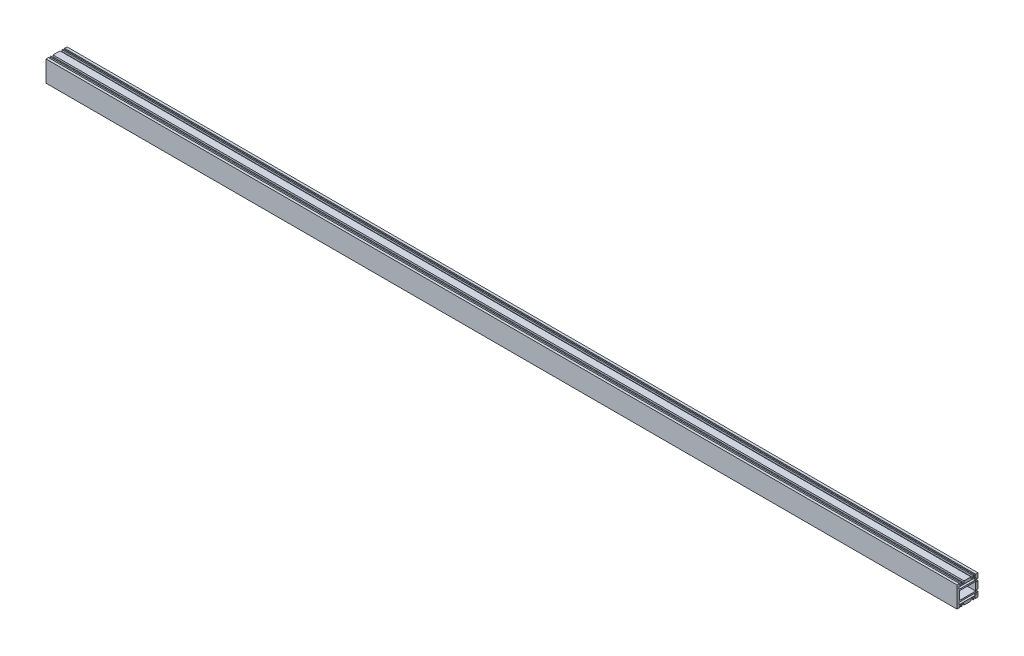
SolidWorks part; units mm, degrees
ref_plane "前视基准面" through (0, 0, 0) normal (0, 0, 1) x (1, 0, 0)
ref_plane "上视基准面" through (0, 0, 0) normal (0, 1, 0) x (1, 0, 0)
ref_plane "右视基准面" through (0, 0, 0) normal (1, 0, 0) x (0, 0, -1)
sketch "草图1" plane through (0, 0, 0) normal (1, 0, 0) x (0, 0, -1)
  line L0 (-15, 15) -> (15, -15) construction
  line L1 (-15, 15) -> (-11.5, 15)
  line L2 (-15, 15) -> (-15, -15)
  line L3 (-15, -15) -> (-11.5, -15)
  line L4 (15, 15) -> (15, 8)
  line L5 (15, 15) -> (-15, -15) construction
  line L6 (-11.5, 15) -> (-11.5, 13.5)
  line L7 (-11.5, 13.5) -> (-11, 13.5)
  line L8 (-11, 13.5) -> (-11, 12)
  line L9 (-11, 12) -> (-9.5, 12)
  line L10 (-9.5, 12) -> (-9.5, 15)
  line L11 (-9.5, 15) -> (-8, 15)
  line L12 (-8, 15) -> (-8, 12.5)
  line L13 (-8, 12.5) -> (-5, 12.5)
  line L14 (-5, 12.5) -> (-5, 15)
  line L15 (-5, 15) -> (5, 15)
  line L16 (0, 21.5201) -> (0, -18.309) construction
  line L17 (0, 55) -> (0, -55) construction
  line L18 (5, 12.5) -> (5, 15)
  line L19 (8, 12.5) -> (5, 12.5)
  line L20 (8, 15) -> (8, 12.5)
  line L21 (9.5, 15) -> (8, 15)
  line L22 (9.5, 12) -> (9.5, 15)
  line L23 (11, 12) -> (9.5, 12)
  line L24 (11, 13.5) -> (11, 12)
  line L25 (11.5, 13.5) -> (11, 13.5)
  line L26 (11.5, 15) -> (11.5, 13.5)
  line L27 (8, 15) -> (9.5, 15)
  line L28 (11.5, 15) -> (15, 15)
  line L29 (-19.8303, 0) -> (22.13, 0) construction
  line L30 (55, 0) -> (-55, 0) construction
  line L31 (8, -15) -> (9.5, -15)
  line L32 (11.5, -15) -> (11.5, -13.5)
  line L33 (11.5, -13.5) -> (11, -13.5)
  line L34 (11, -13.5) -> (11, -12)
  line L35 (11, -12) -> (9.5, -12)
  line L36 (9.5, -12) -> (9.5, -15)
  line L37 (9.5, -15) -> (8, -15)
  line L38 (8, -15) -> (8, -12.5)
  line L39 (8, -12.5) -> (5, -12.5)
  line L40 (5, -12.5) -> (5, -15)
  line L41 (-5, -15) -> (5, -15)
  line L42 (-5, -12.5) -> (-5, -15)
  line L43 (-8, -12.5) -> (-5, -12.5)
  line L44 (-8, -15) -> (-8, -12.5)
  line L45 (-9.5, -15) -> (-8, -15)
  line L46 (-9.5, -12) -> (-9.5, -15)
  line L47 (-11, -12) -> (-9.5, -12)
  line L48 (-11, -13.5) -> (-11, -12)
  line L49 (-11.5, -13.5) -> (-11, -13.5)
  line L50 (-11.5, -15) -> (-11.5, -13.5)
  line L51 (-9.5, -15) -> (-8, -15)
  line L52 (-5, -15) -> (5, -15)
  line L53 (8, -15) -> (9.5, -15)
  line L54 (11.5, -15) -> (15, -15)
  line L55 (15, 8) -> (12.5, 8)
  line L56 (12.5, 8) -> (12.5, 5)
  line L57 (12.5, 5) -> (15, 5)
  line L58 (12.5, -5) -> (15, -5)
  line L59 (12.5, -8) -> (12.5, -5)
  line L60 (15, -8) -> (12.5, -8)
  line L61 (15, 5) -> (15, -5)
  line L62 (15, -8) -> (15, -15)
  line L63 (12, -10.5) -> (12, -8.5)
  line L64 (-11.5, 11) -> (11.5, 11)
  line L65 (-12, 10.5) -> (-12, 8.5)
  line L66 (-11.5, 8) -> (11.5, 8)
  line L67 (12, 10.5) -> (12, 8.5)
  line L68 (-11.5, -8) -> (11.5, -8)
  line L69 (-12, -10.5) -> (-12, -8.5)
  line L70 (-11.5, -11) -> (11.5, -11)
  line L72 (-11.75, 6) -> (11.75, 6)
  line L73 (-11.75, 6) -> (-11.75, -6)
  line L74 (-11.75, -6) -> (11.75, -6)
  line L75 (11.75, 6) -> (11.75, -6)
  arc A0 (12, 8.5) -> (11.5, 8) centre (11.5, 8.5) cw
  arc A1 (11.5, 11) -> (12, 10.5) centre (11.5, 10.5) cw
  arc A2 (-11.5, 11) -> (-12, 10.5) centre (-11.5, 10.5) ccw
  arc A3 (-11.5, 8) -> (-12, 8.5) centre (-11.5, 8.5) cw
  arc A8 (-11.5, -8) -> (-12, -8.5) centre (-11.5, -8.5) ccw
  arc A9 (-11.5, -11) -> (-12, -10.5) centre (-11.5, -10.5) cw
  arc A10 (11.5, -11) -> (12, -10.5) centre (11.5, -10.5) ccw
  arc A11 (12, -8.5) -> (11.5, -8) centre (11.5, -8.5) ccw
  point P69 (12, 11)
  point P72 (-12, 11)
  point P77 (-11, -13.5)
  point P80 (11, -13.5)
  point P83 (11, 13.5)
  point P86 (-11, 13.5)
  point P99 (-12, -11)
  point P100 (12, -11)
  dimension "D17" = 0.5
  dimension "D1" = 3.5
  dimension "D2" = 1.5
  dimension "D3" = 0.5
  dimension "D4" = 1.5
  dimension "D5" = 3
  dimension "D6" = 30
  dimension "D7" = 30
  dimension "D8" = 1.5
  dimension "D9" = 2.5
  dimension "D10" = 3
  dimension "D11" = 2.5
  dimension "D12" = 7
  dimension "D13" = 3
  dimension "D14" = 4
  dimension "D15" = 3
  dimension "D16" = 24
  dimension "D19" = 23.5
  dimension "D20" = 12
extrude "凸台-拉伸1" add sketch "草图1" along normal mid plane 1301
hole_wizard "M6 螺纹孔1" positions "草图3" profile "草图2" tap size "M6" standard "GB"
sketch "草图3" plane through (0, -15, 0) normal (0, -1, 0) x (-1, 0, 0)
  point P0 (615.5, 0)
  point P3 (630.5, 0)
  point P6 (-615.5, 0)
  point P9 (-630.5, 0)
sketch "草图2" plane through (-615.5, -15, 0) normal (1, 0, 0) x (0, 0, -1)
  line L0 (0, 0) -> (0, 20.5022)
  line L1 (0, 20.5022) -> (2.5, 19)
  line L2 (2.5, 19) -> (2.5, 0)
  line L5 (2.5, 0) -> (0, 0)
  line L10 (0, 20.5022) -> (-2.5, 19) construction
  line L11 (0, -6.35) -> (0, 107.95) construction
  dimension "螺纹孔钻头直径" = 5
  dimension "螺纹孔钻头深度" = 19
  dimension "导头角度" = 118
cosmetic thread "孔螺蚊线1" parameters "D1"=9, "D2"=6
cosmetic thread "孔螺蚊线2" parameters "D1"=9, "D2"=6
cosmetic thread "孔螺蚊线3" parameters "D1"=9, "D2"=6
cosmetic thread "孔螺蚊线4" parameters "D1"=9, "D2"=6
hole_wizard "M6 螺纹孔2" positions "草图5" profile "草图4" tap size "M6" standard "GB"
sketch "草图5" plane through (0, 0, -15) normal (0, 0, -1) x (-1, 0, 0)
  point P0 (-630.5, 0)
  point P3 (-615.5, 0)
  point P6 (630.5, 0)
  point P9 (615.5, 0)
sketch "草图4" plane through (630.5, 0, -15) normal (1, 0, 0) x (0, 1, 0)
  line L0 (0, 0) -> (0, 20.5022)
  line L1 (0, 20.5022) -> (2.5, 19)
  line L2 (2.5, 19) -> (2.5, 0)
  line L5 (2.5, 0) -> (0, 0)
  line L10 (0, 20.5022) -> (-2.5, 19) construction
  line L11 (0, -6.35) -> (0, 107.95) construction
  dimension "螺纹孔钻头直径" = 5
  dimension "螺纹孔钻头深度" = 19
  dimension "导头角度" = 118
cosmetic thread "孔螺蚊线5" parameters "D1"=3.25, "D2"=6
cosmetic thread "孔螺蚊线6" parameters "D1"=3.25, "D2"=6
cosmetic thread "孔螺蚊线7" parameters "D1"=3.25, "D2"=6
cosmetic thread "孔螺蚊线8" parameters "D1"=3.25, "D2"=6
hole_wizard "M4 螺纹孔1" positions "草图7" profile "草图6" tap size "M4" standard "GB"
sketch "草图7" plane through (0, 0, -15) normal (0, 0, -1) x (-1, 0, 0)
  line L0 (-650.5, -15) -> (650.5, -15) construction
  line L1 (-650.5, 5) -> (-650.5, -5) construction
  point P0 (560, 0)
  point P2 (280, 0)
  point P4 (0, 0)
  point P6 (-280, 0)
  point P8 (-560, 0)
  dimension "D1" = 15
  dimension "D2" = 90.5
  dimension "D3" = 15
  dimension "D4" = 280
  dimension "D5" = 280
  dimension "D6" = 15
  dimension "D7" = 280
  dimension "D8" = 15
  dimension "D9" = 280
  dimension "D10" = 15
sketch "草图6" plane through (-560, 0, -15) normal (1, 0, 0) x (0, 1, 0)
  line L0 (0, 0) -> (0, 15.9914)
  line L1 (0, 15.9914) -> (1.65, 15)
  line L2 (1.65, 15) -> (1.65, 0)
  line L5 (1.65, 0) -> (0, 0)
  line L10 (0, 15.9914) -> (-1.65, 15) construction
  line L11 (0, -6.35) -> (0, 107.95) construction
  dimension "螺纹孔钻头直径" = 3.3
  dimension "螺纹孔钻头深度" = 15
  dimension "导头角度" = 118
cosmetic thread "孔螺蚊线9" parameters "D1"=3.25, "D2"=4
cosmetic thread "孔螺蚊线10" parameters "D1"=3.25, "D2"=4
cosmetic thread "孔螺蚊线11" parameters "D1"=3.25, "D2"=4
cosmetic thread "孔螺蚊线12" parameters "D1"=3.25, "D2"=4
cosmetic thread "孔螺蚊线13" parameters "D1"=3.25, "D2"=4
